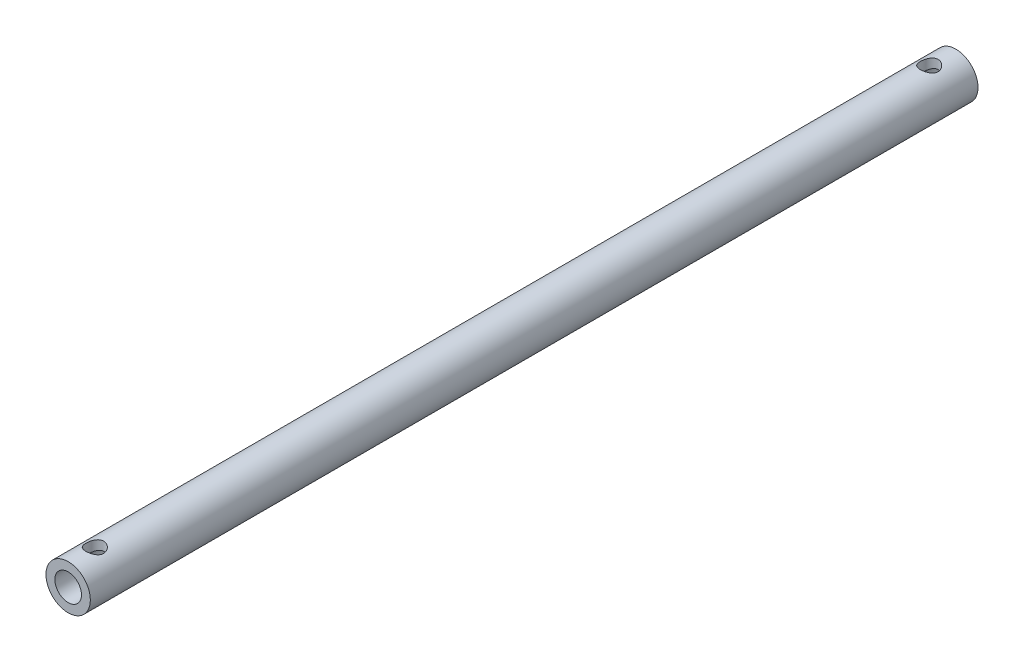
SolidWorks part; units mm, degrees
ref_plane "Plan de face" through (0, 0, 0) normal (0, 0, 1) x (1, 0, 0)
ref_plane "Plan de dessus" through (0, 0, 0) normal (0, 1, 0) x (1, 0, 0)
ref_plane "Plan de droite" through (0, 0, 0) normal (1, 0, 0) x (0, 0, -1)
sketch "Esquisse1" plane through (0, 0, 0) normal (0, 0, 1) x (1, 0, 0)
  circle A0 centre (-4.9182, 1.1045) radius 2.5
  circle A1 centre (-4.9182, 1.1045) radius 1.5
  dimension "D1" = 3
  dimension "D2" = 5
extrude "Boss.-Extru.1" add sketch "Esquisse1" along normal blind 100
ref_plane "Plan1" through (0, 3.6045, 0) normal (0, 1, 0) x (1, 0, 0)
sketch "Esquisse2" plane through (0, 3.6045, 0) normal (0, 1, 0) x (1, 0, 0)
  line L0 (-4.9182, 0) -> (-4.9182, -100) construction
  line L1 (-2.4182, 0) -> (-7.4182, 0) construction
  line L2 (-7.4182, -100) -> (-2.4182, -100) construction
  circle A0 centre (-4.9182, -3) radius 1
  circle A1 centre (-4.9182, -97) radius 1
  dimension "D2" = 2
  dimension "D3" = 2
  dimension "D1" = 3
  dimension "D4" = 3
extrude "Enlèv. mat.-Extru.1" cut sketch "Esquisse2" against normal through all
